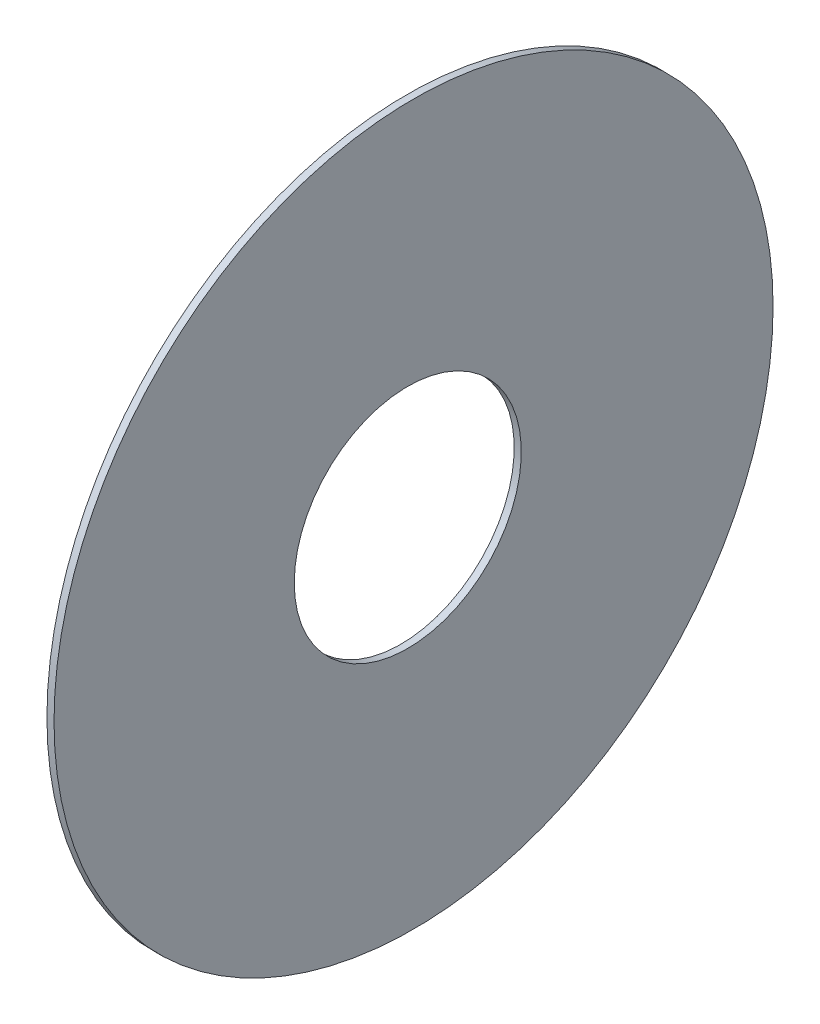
SolidWorks part; units mm, degrees
ref_plane "Front Plane" through (0, 0, 0) normal (0, 0, 1) x (1, 0, 0)
ref_plane "Top Plane" through (0, 0, 0) normal (0, 1, 0) x (1, 0, 0)
ref_plane "Right Plane" through (0, 0, 0) normal (1, 0, 0) x (0, 0, -1)
sketch "Sketch1" plane through (0, 0, 0) normal (1, 0, 0) x (0, 0, -1)
  circle A0 centre (3.8698, 0) radius 241.3
  circle A1 centre (0, 0) radius 76.2
  dimension "D1" = 482.6
  dimension "D2" = 152.4
extrude "Boss-Extrude1" add sketch "Sketch1" along normal blind 4.7625
